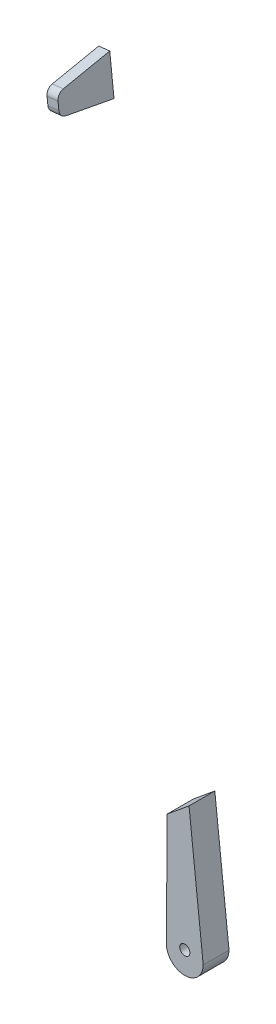
SolidWorks part; units mm, degrees
ref_plane "Front Plane" through (0, 0, 0) normal (0, 0, 1) x (1, 0, 0)
ref_plane "Top Plane" through (0, 0, 0) normal (0, 1, 0) x (1, 0, 0)
ref_plane "Right Plane" through (0, 0, 0) normal (1, 0, 0) x (0, 0, -1)
ref_plane "Plane1" through (0, 0, 686.8092) normal (0, 0, 1) x (1, 0, 0)
sketch "Sketch1" plane through (0, 0, 686.8092) normal (0, 0, 1) x (1, 0, 0)
  line L10 (3684.3457, -2118.2051) -> (3696.7821, -2117.9891) construction
  line L11 (1900.8889, 19.6204) -> (1896.0011, 64.6934)
  line L15 (1888.1657, 19.7492) -> (1888.4918, 58.498)
  circle A3 centre (1894.5376, 20.9548) radius 1.7526
  arc A5 (1896.0011, 64.6934) -> (1888.4918, 58.498) centre (3690.5639, -2118.0971) ccw
  arc A6 (1900.8889, 19.6204) -> (1888.1657, 19.7492) centre (1894.5273, 19.6848) cw
extrude "Boss-Extrude1" add sketch "Sketch1" along normal blind 8.89
sketch "Sketch2" plane through (1880.9014, 203.9354, 0) normal (-0.9942, -0.1078, 0) x (0, 0, 1)
  line L0 (695.6087, 73.2446) -> (695.6076, 70.2539)
  line L5 (711.9308, 62.5437) -> (695.604, 59.6866)
  line L6 (695.6087, 73.2446) -> (697.909, 72.8236)
  line L13 (714.033, 67.7554) -> (714.033, 65.0457)
  line L14 (711.9502, 70.2539) -> (695.6087, 73.2446)
  line L16 (695.6087, 73.2446) -> (695.604, 59.6866)
  arc A1 (711.9502, 70.2539) -> (714.033, 67.7554) centre (711.493, 67.7554) cw
  arc A2 (714.033, 65.0457) -> (711.9308, 62.5437) centre (711.493, 65.0457) cw
  dimension "D1" = 2.54
  dimension "D2" = 2.54
extrude "Boss-Extrude2" add sketch "Sketch2" along normal blind 1.905 and the other way blind 1.905 from offset 6.35
